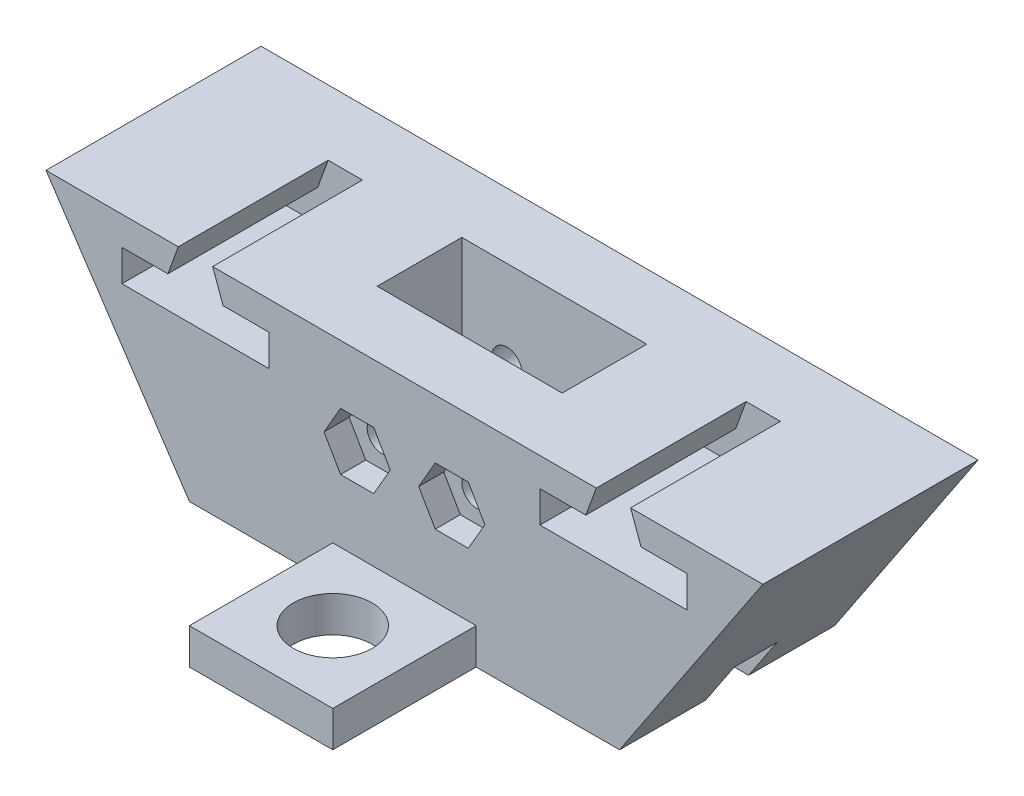
SolidWorks part; units mm, degrees
ref_plane "Front Plane" through (0, 0, 0) normal (0, 0, 1) x (1, 0, 0)
ref_plane "Top Plane" through (0, 0, 0) normal (0, 1, 0) x (1, 0, 0)
ref_plane "Right Plane" through (0, 0, 0) normal (1, 0, 0) x (0, 0, -1)
sketch "Sketch1" plane through (0, 0, 0) normal (0, 0, 1) x (1, 0, 0)
  line L1 (0, 0) -> (20, 0)
  line L2 (0, 0) -> (0, 15)
  line L3 (0, 15) -> (20, 15)
  line L4 (20, 0) -> (20, 15)
  dimension "D1" = 20
  dimension "D2" = 15
extrude "SwitchCase" add sketch "Sketch1" along normal blind 15
sketch "Sketch2" plane through (0, 15, 0) normal (0, 1, 0) x (1, 0, 0)
  line L0 (0, -15) -> (0, 0) construction
  line L1 (3.55, -4.55) -> (16.45, -4.55)
  line L2 (3.55, -4.55) -> (3.55, -10.45)
  line L3 (3.55, -10.45) -> (16.45, -10.45)
  line L4 (16.45, -4.55) -> (16.45, -10.45)
  line L5 (20, 0) -> (0, 0) construction
  point P6 (10, -4.55)
  point P9 (3.55, -7.5)
  dimension "D1" = 5.9
  dimension "D2" = 12.9
  dimension "D3" = 10
  dimension "D4" = 7.5
extrude "SwitchCavity" cut sketch "Sketch2" against normal through all
sketch "Sketch3" plane through (0, 0, 4.55) normal (0, 0, 1) x (1, 0, 0)
  line L0 (3.55, 0) -> (3.55, 15) construction
  line L1 (16.45, 0) -> (16.45, 15) construction
  line L3 (20, 15) -> (0, 15) construction
  line L4 (16.45, 15) -> (3.55, 15) construction
  circle A0 centre (6.7, 8.9) radius 1.05
  circle A1 centre (13.3, 8.9) radius 1.05
  dimension "D1" = 2.1
  dimension "D2" = 3.15
  dimension "D3" = 3.15
  dimension "D4" = 6.1
  dimension "D5" = 6.1
extrude "SwitchM2Holes" cut sketch "Sketch3" against normal through all both and the other way through all
sketch "Sketch5" plane through (0, 0, 15) normal (0, 0, 1) x (1, 0, 0)
  line L1 (9.0094, 8.9) -> (7.8547, 10.9)
  line L2 (7.8547, 10.9) -> (5.5453, 10.9)
  line L3 (5.5453, 10.9) -> (4.3906, 8.9)
  line L4 (4.3906, 8.9) -> (5.5453, 6.9)
  line L5 (5.5453, 6.9) -> (7.8547, 6.9)
  line L6 (7.8547, 6.9) -> (9.0094, 8.9)
  line L8 (15.6094, 8.9) -> (14.4547, 10.9)
  line L9 (14.4547, 10.9) -> (12.1453, 10.9)
  line L10 (12.1453, 10.9) -> (10.9906, 8.9)
  line L11 (10.9906, 8.9) -> (12.1453, 6.9)
  line L12 (12.1453, 6.9) -> (14.4547, 6.9)
  line L13 (14.4547, 6.9) -> (15.6094, 8.9)
  circle A0 centre (6.7, 8.9) radius 2 construction
  circle A1 centre (13.3, 8.9) radius 2 construction
  dimension "D1" = 4
  dimension "D2" = 2
extrude "NutInserts" cut sketch "Sketch5" against normal blind 1.75 and the other way through all
sketch "Sketch4" plane through (0, 0, 0) normal (0, -1, 0) x (1, 0, 0)
  line L0 (0, 15) -> (20, 15) construction
  line L1 (5, 15) -> (15, 15)
  line L2 (5, 15) -> (5, 25)
  line L3 (5, 25) -> (15, 25)
  line L4 (15, 15) -> (15, 25)
  line L5 (0, 0) -> (20, 0) construction
  line L6 (5, 0) -> (15, 0)
  line L7 (5, 0) -> (5, -10)
  line L8 (5, -10) -> (15, -10)
  line L9 (15, 0) -> (15, -10)
  line L10 (0, 15) -> (0, 0) construction
  dimension "D1" = 5
  dimension "D2" = 10
  dimension "D3" = 5
extrude "MountTabs" add sketch "Sketch4" against normal blind 2.5
sketch "Sketch6" plane through (0, 2.5, 0) normal (0, 1, 0) x (1, 0, 0)
  line L0 (15, -15) -> (15, -25) construction
  line L1 (15, -25) -> (5, -25) construction
  line L2 (5, 10) -> (15, 10) construction
  circle A0 centre (10, -20) radius 2.75
  circle A1 centre (10, 5) radius 2.75
  point P4 (0, 0)
  dimension "D1" = 5.5
  dimension "D2" = 5
  dimension "D3" = 5
  dimension "D4" = 5
extrude "M5ScrewHoles" cut sketch "Sketch6" against normal up to next
sketch "Sketch7" plane through (0, 0, 15) normal (0, 0, 1) x (1, 0, 0)
  line L0 (0, 15) -> (-15, 15)
  line L2 (0, 0) -> (0, 15)
  line L3 (20, 15) -> (35, 15)
  line L5 (20, 0) -> (20, 15)
  line L6 (0, 0) -> (-5, 0)
  line L7 (-5, 0) -> (-15, 15)
  line L8 (20, 0) -> (25, 0)
  line L9 (25, 0) -> (35, 15)
  dimension "D1" = 15
  dimension "D2" = 5
extrude "Wings" add sketch "Sketch7" against normal up to surface (15 mm away) up to face at (10, 4.375, 0)
sketch "Sketch8" plane through (16.45, 0, 0) normal (-1, 0, 0) x (0, 0, 1)
  line L0 (10.45, 0) -> (4.55, 0) construction
  line L1 (6, 0) -> (9, 0)
  line L2 (6, 0) -> (6, 3)
  line L3 (6, 3) -> (9, 3)
  line L4 (9, 0) -> (9, 3)
  line L5 (10.45, 0) -> (10.45, 15) construction
  point P6 (7.5, 0)
  dimension "D1" = 3
  dimension "D2" = 3
  dimension "D3" = 2.95
extrude "WireChannel" cut sketch "Sketch8" against normal through all both and the other way through all
sketch "Sketch9" plane through (0, 0, 15) normal (0, 0, 1) x (1, 0, 0)
  line L0 (-9.7, 10.8) -> (0.55, 10.8)
  line L1 (0.55, 10.8) -> (0.55, 13)
  line L2 (0.55, 13) -> (-2.65, 13)
  line L3 (-2.65, 13) -> (-3.3779, 15)
  line L4 (35, 15) -> (-15, 15) construction
  line L5 (-3.3779, 15) -> (-5.7721, 15)
  line L6 (-5.7721, 15) -> (-6.5, 13)
  line L7 (-6.5, 13) -> (-9.7, 13)
  line L8 (-9.7, 13) -> (-9.7, 10.8)
  line L10 (3.55, 0) -> (3.55, 15) construction
  line L11 (10, 15) -> (10, -1.0272) construction
  line L12 (35, 15) -> (-15, 15) construction
  line L13 (26.5, 13) -> (29.7, 13)
  line L14 (25.7721, 15) -> (26.5, 13)
  line L15 (23.3779, 15) -> (25.7721, 15)
  line L16 (22.65, 13) -> (23.3779, 15)
  line L17 (19.45, 13) -> (22.65, 13)
  line L18 (19.45, 10.8) -> (19.45, 13)
  line L19 (29.7, 10.8) -> (19.45, 10.8)
  line L20 (29.7, 13) -> (29.7, 10.8)
  dimension "D1" = 10.25
  dimension "D2" = 2.2
  dimension "D3" = 3.2
  dimension "D4" = 110
  dimension "D5" = 110
  dimension "D6" = 2
  dimension "D7" = 3
extrude "BumperChannel" cut sketch "Sketch9" against normal up to vertex (10.45 mm away) and the other way through all
